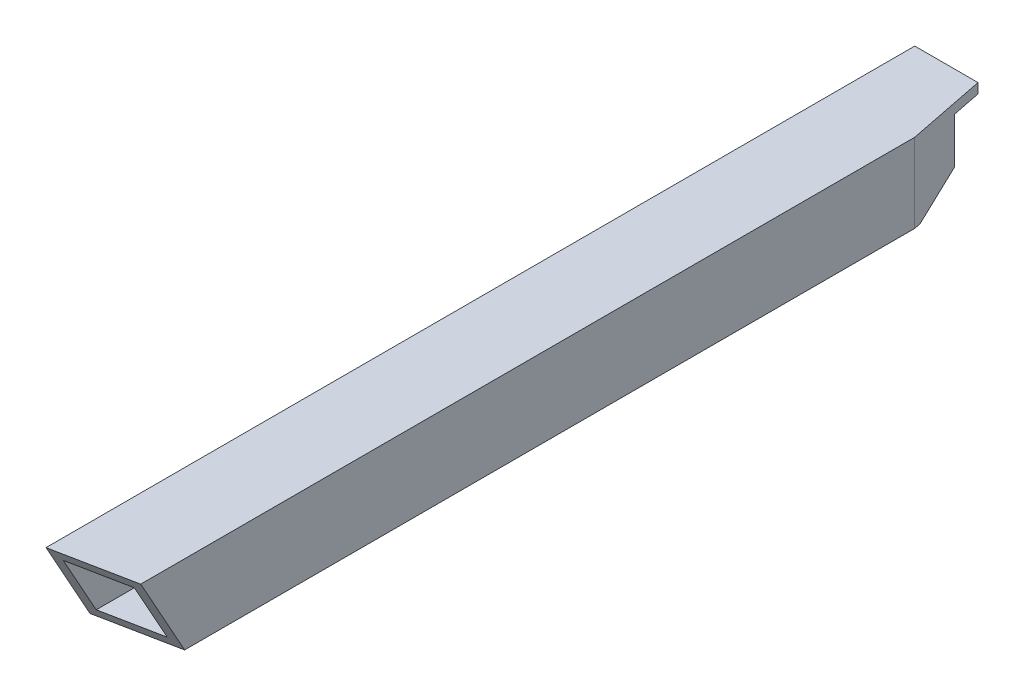
SolidWorks part; units mm, degrees
material "6061 Alloy"
ref_plane "Front Plane" through (0, 0, 0) normal (0, 0, 1) x (1, 0, 0)
ref_plane "Top Plane" through (0, 0, 0) normal (0, 1, 0) x (1, 0, 0)
ref_plane "Right Plane" through (0, 0, 0) normal (1, 0, 0) x (0, 0, -1)
sketch "Sketch1" plane through (0, 0, 0) normal (0, 0, 1) x (1, 0, 0)
  line L0 (12.7, 0) -> (9.525, 0) construction
  line L1 (-12.7, 0) -> (12.7, 0) construction
  line L2 (0, 12.7) -> (0, -12.7)
  point P7 (0, 0)
sketch "Sketch2" plane through (0, 0, 0) normal (1, 0, 0) x (0, 0, -1)
  line L0 (139.7, 0) -> (-139.7, 0)
  point P4 (0, 0)
  dimension "Length" = 279.4
sketch "Sketch3" plane through (0, 0, 0) normal (0, 0, 1) x (1, 0, 0)
  line L0 (-12.7, 0) -> (12.7, 0) construction
  line L5 (12.7, -12.7) -> (-12.7, -12.7)
  line L6 (12.7, -12.7) -> (12.7, 12.7)
  line L11 (12.7, 12.7) -> (-12.7, 12.7)
  line L12 (-12.7, -12.7) -> (-12.7, 12.7)
  line L14 (12.7, -12.7) -> (-12.7, 12.7) construction
  line L15 (12.7, 12.7) -> (-12.7, -12.7) construction
  line L16 (9.525, -9.525) -> (-9.525, -9.525)
  line L17 (9.525, -9.525) -> (9.525, 9.525)
  line L18 (9.525, 9.525) -> (-9.525, 9.525)
  line L19 (-9.525, -9.525) -> (-9.525, 9.525)
  line L20 (9.525, -9.525) -> (-9.525, 9.525) construction
  line L21 (9.525, 9.525) -> (-9.525, -9.525) construction
  point P0 (0, 0)
  point P5 (0, 0)
  point P13 (9.525, -12.7)
  dimension "D1" = 3.175
  dimension "D3" = 25.4
  dimension "D4" = 25.4
extrude "Boss-Extrude1" add sketch "Sketch3" along normal up to vertex (139.7 mm away) and the other way up to vertex (139.7 mm away) up to point (0, 0, 139.7) other way up to point (0, 0, -139.7)
sketch "Sketch5" plane through (0, 0, 0) normal (1, 0, 0) x (0, 0, -1)
  line L0 (-139.7, 0) -> (139.7, 0) construction
  line L3 (-139.7, -12.7) -> (-139.7, 12.7) construction
  line L4 (139.7, -12.7) -> (139.7, 12.7) construction
  point P6 (-111.125, 0)
  point P7 (-101.6, 0)
  point P8 (101.6, 0)
  point P10 (111.125, 0)
  dimension "D1" = 28.575
  dimension "D2" = 38.1
  dimension "D3" = 28.575
  dimension "D4" = 38.1
sketch "Sketch7" plane through (0, 12.7, 0) normal (0, -1, 0) x (1, 0, 0)
  line L0 (-12.7, 139.7) -> (12.7, 134.643) construction
  line L1 (12.7, 139.7) -> (12.7, -139.7) construction
  line L2 (-12.7, 139.7) -> (12.7, 139.7) construction
  dimension "D1" = 11.26
ref_plane "Plane2" through (26.2687, 0, 131.9416) normal (0.1953, 0, 0.9808) x (0, -1, 0)
ref_plane "Plane3" through (19.2031, -53.6419, 96.4523) normal (0.1714, -0.4788, 0.861) x (0.9808, 0, -0.1953)
other "SurfaceCut2"
sketch "Sketch8" plane through (0, -12.7, 0) normal (0, -1, 0) x (1, 0, 0)
  line L0 (12.7, -114.3) -> (7.643, -139.7) construction
  line L1 (12.7, 120.5168) -> (12.7, -139.7) construction
  line L2 (-12.7, -139.7) -> (12.7, -139.7) construction
  dimension "D1" = 11.26
  dimension "D2" = 25.4
sketch "Sketch10" plane through (-12.7, 0, 0) normal (-1, 0, 0) x (0, 0, 1)
  line L0 (-114.3, -12.7) -> (-139.7, -0.4885) construction
  line L1 (125.5738, -12.7) -> (-139.7, -12.7) construction
  line L2 (-139.7, 12.7) -> (-139.7, -12.7) construction
  dimension "D1" = 25.677
  dimension "D2" = 25.4
sketch "Sketch9" plane through (0, 0, -139.7) normal (0, 0, -1) x (-1, 0, 0)
  line L0 (-7.643, -12.7) -> (-7.643, 12.7) construction
  line L1 (-12.7, 12.7) -> (12.7, 12.7) construction
  line L2 (12.7, -0.4885) -> (-12.7, 0) construction
  line L3 (-12.7, -12.7) -> (-12.7, 12.7) construction
ref_plane "Plane4" through (34.1046, 0, -6.79) normal (0.9808, 0, -0.1953) x (0, 1, 0)
other "SurfaceCut4"
ref_plane "Plane5" through (1.1324, -58.8785, -32.095) normal (0.0169, -0.8779, -0.4785) x (0.9998, 0.0192, 0)
other "SurfaceCut6"
equation "\"D1@Sketch3\"=\"Wall thickness@Sketch1\""
equation "\"D1@Sketch5\"=\"Width@Sketch1\"*1.125"
equation "\"D2@Sketch5\"=\"Width@Sketch1\"*1.5"
equation "\"D3@Sketch5\"=\"D1@Sketch5\""
equation "\"D4@Sketch5\"=\"D2@Sketch5\""
equation "\"D2@Sketch3\"=\"Wall Thickness@Sketch1\""
